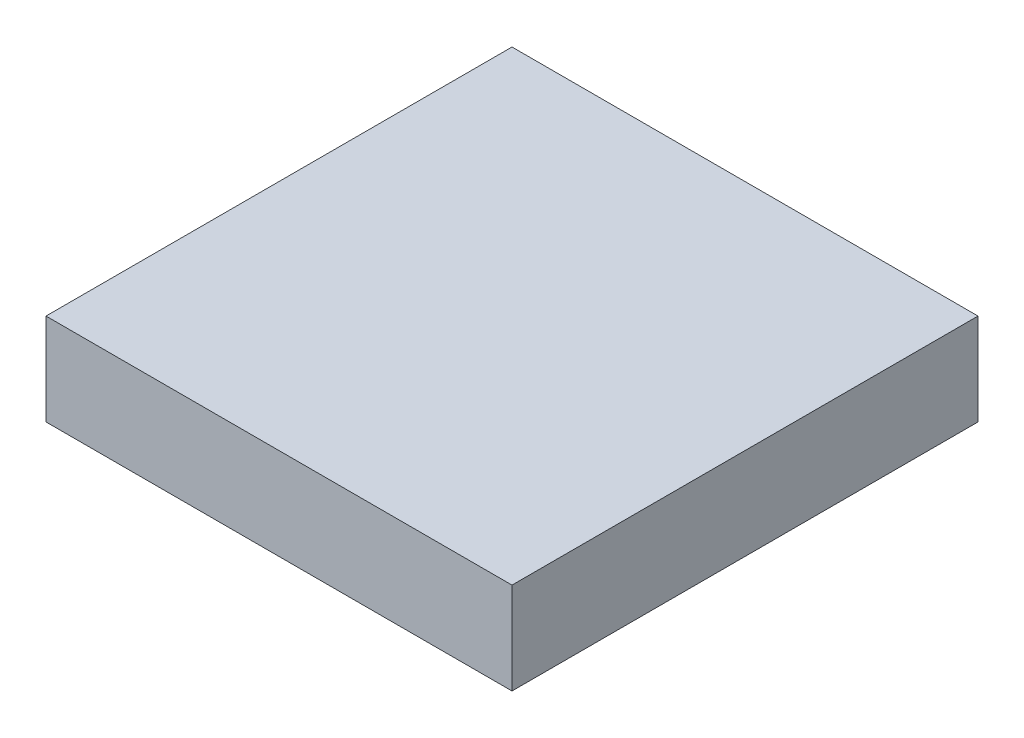
SolidWorks part; units mm, degrees
ref_plane "Front Plane" through (0, 0, 0) normal (0, 0, 1) x (1, 0, 0)
ref_plane "Top Plane" through (0, 0, 0) normal (0, 1, 0) x (1, 0, 0)
ref_plane "Right Plane" through (0, 0, 0) normal (1, 0, 0) x (0, 0, -1)
sketch "Sketch1" plane through (0, 0, 0) normal (0, 1, 0) x (1, 0, 0)
  line L1 (-12.7, 12.7) -> (12.7, 12.7)
  line L2 (-12.7, 12.7) -> (-12.7, -12.7)
  line L3 (-12.7, -12.7) -> (12.7, -12.7)
  line L4 (12.7, 12.7) -> (12.7, -12.7)
  line L5 (-12.7, 12.7) -> (12.7, -12.7) construction
  line L6 (-12.7, -12.7) -> (12.7, 12.7) construction
  point P0 (0, 0)
  dimension "D1" = 25.4
  dimension "D2" = 25.4
extrude "Boss-Extrude1" add sketch "Sketch1" along normal blind 5
